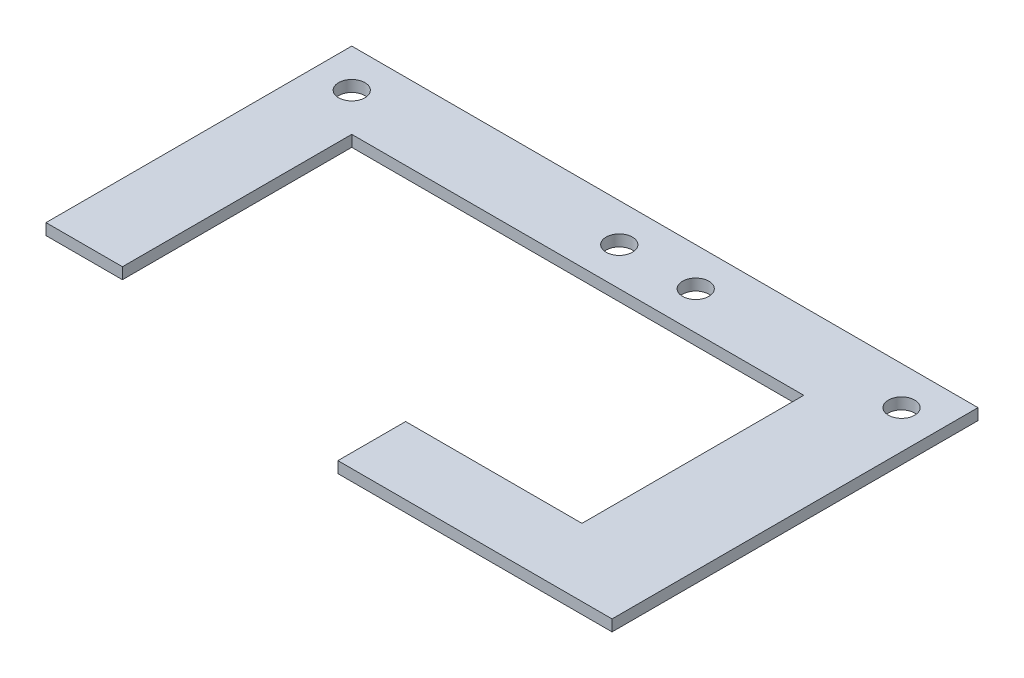
SolidWorks part; units mm, degrees
ref_plane "Front Plane" through (0, 0, 0) normal (0, 0, 1) x (1, 0, 0)
ref_plane "Top Plane" through (0, 0, 0) normal (0, 1, 0) x (1, 0, 0)
ref_plane "Right Plane" through (0, 0, 0) normal (1, 0, 0) x (0, 0, -1)
sketch "Sketch1" plane through (0, 0, 0) normal (0, 1, 0) x (1, 0, 0)
  line L0 (5.08, -43.56) -> (-31.36, -43.56)
  line L1 (5.08, -43.56) -> (5.08, 5.08)
  line L2 (-7.92, -34.56) -> (-31.36, -34.56)
  line L3 (-7.92, -34.56) -> (-7.92, -5.08)
  line L4 (-7.92, -43.56) -> (-7.92, 5.08) construction
  line L5 (5.08, -34.56) -> (-31.36, -34.56) construction
  line L6 (-31.36, -34.56) -> (-31.36, -43.56)
  line L7 (5.08, 5.08) -> (-78.16, 5.08)
  line L9 (-78.16, 5.08) -> (-78.16, -35.56)
  line L10 (-68, -5.08) -> (-68, -35.56)
  line L11 (-7.92, -5.08) -> (-68, -5.08)
  line L12 (-68, 5.08) -> (-68, -35.56) construction
  line L13 (-68, -35.56) -> (-78.16, -35.56)
  circle A0 centre (0, 0) radius 1.75
  circle A1 centre (-73.08, 0) radius 1.75
  circle A2 centre (-27.36, 0) radius 1.75
  circle A3 centre (-37.52, 0) radius 1.75
  dimension "D1" = 5.08
  dimension "D7" = 73.08
  dimension "D10" = 3.5
  dimension "D11" = 3.5
  dimension "D13" = 10.16
  dimension "D2" = 5.08
  dimension "D3" = 48.64
  dimension "D4" = 36.44
  dimension "D8" = 5.08
  dimension "D12" = 27.36
  dimension "D9" = 40.64
  dimension "D5" = 9
  dimension "D6" = 13
  dimension "D14" = 10.16
extrude "Boss-Extrude1" add sketch "Sketch1" along normal blind 1.5
